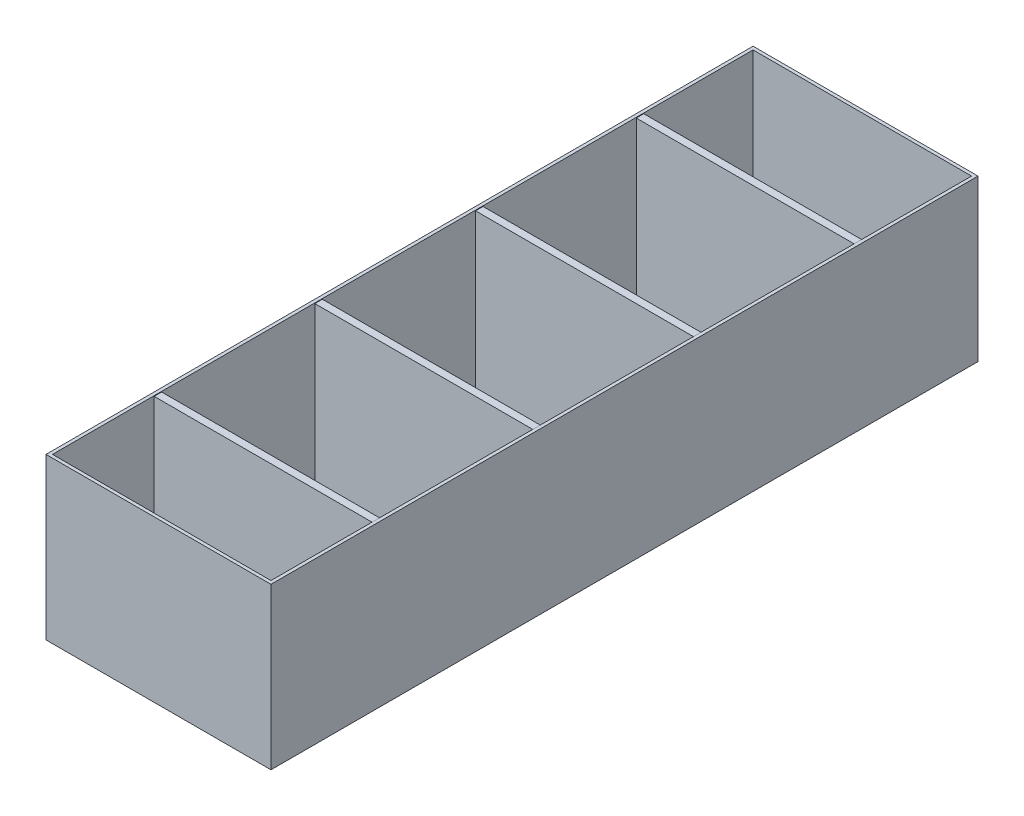
SolidWorks part; units mm, degrees
ref_plane "Alzado" through (0, 0, 0) normal (0, 0, 1) x (1, 0, 0)
ref_plane "Planta" through (0, 0, 0) normal (0, 1, 0) x (1, 0, 0)
ref_plane "Vista lateral" through (0, 0, 0) normal (1, 0, 0) x (0, 0, -1)
sketch "Croquis1" plane through (0, 0, 0) normal (0, 0, 1) x (1, 0, 0)
  line L1 (-350, 250) -> (350, 250)
  line L2 (-350, 250) -> (-350, -250)
  line L3 (-350, -250) -> (350, -250)
  line L4 (350, 250) -> (350, -250)
  line L5 (-350, 250) -> (350, -250) construction
  line L6 (-350, -250) -> (350, 250) construction
  point P0 (0, 0)
  dimension "D1" = 700
  dimension "D2" = 500
extrude "Saliente-Extruir1" add sketch "Croquis1" along normal blind 2200
shell "Vaciado1" thickness 10
sketch "Croquis2" plane through (0, -240, 0) normal (0, 1, 0) x (1, 0, 0)
  line L0 (-340, -350.033) -> (340, -350.033)
  line L1 (-340, -2190) -> (-340, -10) construction
  line L2 (340, -2190) -> (340, -10) construction
  line L3 (340, -350.033) -> (340, -373.3524)
  line L4 (340, -373.3524) -> (-340, -373.3524)
  line L5 (-340, -373.3524) -> (-340, -350.033)
extrude "Saliente-Extruir2" add sketch "Croquis2" along normal blind 488
pattern_linear "MatrizL1" count 4 spacing 500 along (0, 0, 1) of "Saliente-Extruir2"
